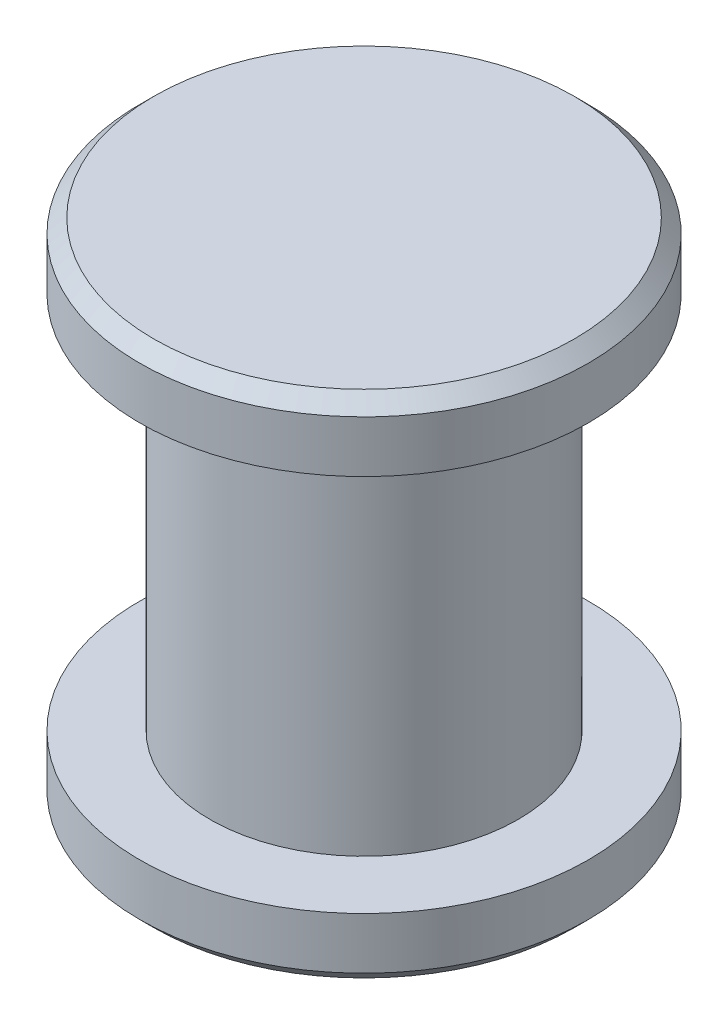
SolidWorks part; units mm, degrees
ref_plane "Front" through (0, 0, 0) normal (0, 0, 1) x (1, 0, 0)
ref_plane "Top" through (0, 0, 0) normal (0, 1, 0) x (1, 0, 0)
ref_plane "Right" through (0, 0, 0) normal (1, 0, 0) x (0, 0, -1)
sketch "Sketch1" plane through (0, 0, 0) normal (0, 0, 1) x (1, 0, 0)
  line L0 (0, 0) -> (0, 9.0949) construction
  line L1 (0, 9.0949) -> (-4, 9.0949)
  line L2 (-4, 9.0949) -> (-4, 7.9224)
  line L3 (-4, 7.9224) -> (-2.75, 7.9224)
  line L4 (-2.75, 7.9224) -> (-2.75, 1.1724)
  line L5 (-2.75, 1.1724) -> (-4, 1.1724)
  line L6 (-4, 1.1724) -> (-4, 0)
  line L7 (-4, 0) -> (0, 0)
  line L8 (0, 0) -> (0, 9.0949)
  dimension "D1" = 6.75
  dimension "D2" = 2.75
  dimension "D3" = 4
revolve "Revolve1" add sketch "Sketch1" angle 360 about L0
chamfer "Chamfer1" distance 0.25 angle 45 2 edges at (4, 0, 0) (4, 9.0949, 0)
